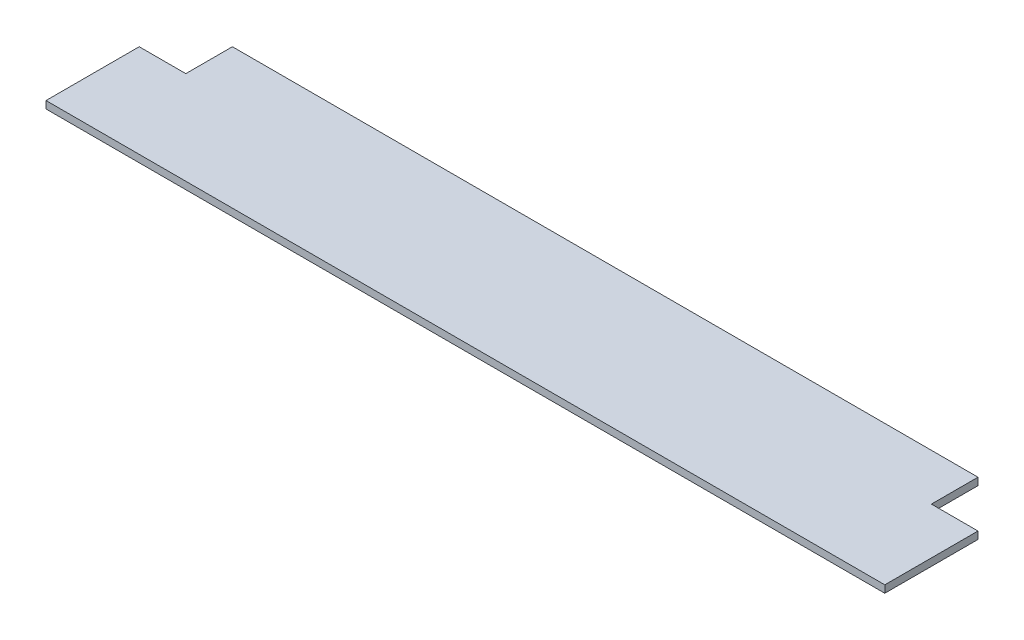
SolidWorks part; units mm, degrees
ref_plane "Front Plane" through (0, 0, 0) normal (0, 0, 1) x (1, 0, 0)
ref_plane "Top Plane" through (0, 0, 0) normal (0, 1, 0) x (1, 0, 0)
ref_plane "Right Plane" through (0, 0, 0) normal (1, 0, 0) x (0, 0, -1)
sketch "Sketch1" plane through (0, 0, 0) normal (0, 1, 0) x (1, 0, 0)
  line L0 (-50.8, 6.35) -> (-50.8, 12.7)
  line L1 (-57.15, -6.35) -> (57.15, -6.35)
  line L2 (-57.15, -6.35) -> (-57.15, 6.35)
  line L3 (-57.15, 6.35) -> (-50.8, 6.35)
  line L4 (57.15, -6.35) -> (57.15, 6.35)
  line L5 (-57.15, -6.35) -> (57.15, 6.35) construction
  line L6 (-57.15, 6.35) -> (57.15, -6.35) construction
  line L7 (-50.8, 12.7) -> (50.8, 12.7)
  line L8 (50.8, 12.7) -> (50.8, 6.35)
  line L9 (50.8, 6.35) -> (57.15, 6.35)
  point P0 (0, 0)
  point P10 (0, 12.7)
  dimension "D1" = 12.7
  dimension "D2" = 114.3
  dimension "D3" = 6.35
  dimension "D4" = 101.6
extrude "Boss-Extrude1" add sketch "Sketch1" along normal blind 1
